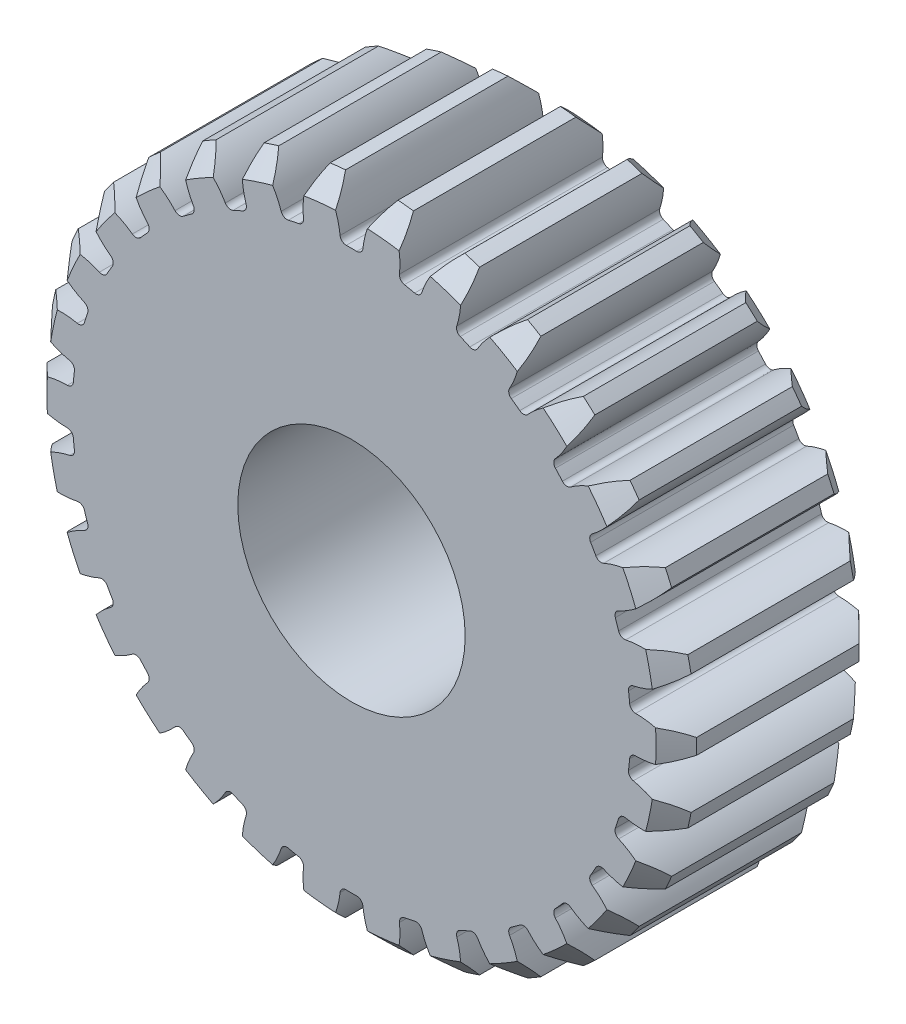
SolidWorks part; units mm, degrees
material "Plain Carbon Steel"
ref_plane "Front Plane" through (0, 0, 0) normal (0, 0, 1) x (1, 0, 0)
ref_plane "Top Plane" through (0, 0, 0) normal (0, 1, 0) x (1, 0, 0)
ref_plane "Right Plane" through (0, 0, 0) normal (1, 0, 0) x (0, 0, -1)
sketch "Sketch1" plane through (0, 0, 0) normal (0, 0, 1) x (1, 0, 0)
  circle A0 centre (0, 0) radius 30 construction
  circle A1 centre (0, 0) radius 32
  dimension "D1" = 60
  dimension "D2" = 64
extrude "Boss-Extrude1" add sketch "Sketch1" along normal mid plane 20
sketch "Sketch2" plane through (0, 0, 10) normal (0, 0, 1) x (1, 0, 0)
  line L0 (0, 0) -> (0, 32) construction
  line L1 (0, 0) -> (6.6532, 31.3007) construction
  line L2 (0, 0) -> (3.3449, 31.8247) construction
  line L3 (-1.0822, 27.4787) -> (0, 0) construction
  line L4 (-1.5701, 29.9589) -> (1.5701, 29.9589) construction
  line L5 (1.5701, 29.9589) -> (4.693, 29.6307) construction
  line L6 (-2.2833, 31.9184) -> (0, 25.6451) construction
  circle A0 centre (0, 0) radius 28 construction
  circle A2 centre (0, 0) radius 32 construction
  arc A3 (-2.5853, 31.8954) -> (-1.0822, 27.4787) centre (-9.2704, 27.1562) cw
  circle A4 centre (0, 0) radius 32 construction
  arc A5 (2.5853, 31.8954) -> (1.0822, 27.4787) centre (9.2704, 27.1562) ccw
  circle A6 centre (0, 0) radius 30 construction
  arc A8 (2.5853, 31.8954) -> (-2.5853, 31.8954) centre (0, 0) ccw
  arc A9 (1.0822, 27.4787) -> (-1.0822, 27.4787) centre (0, 0) ccw
  dimension "D1" = 12
  dimension "D2" = 4
  dimension "D5" = 20
  dimension "D3" = 0.5
extrude "Cut-Extrude1" cut sketch "Sketch2" against normal through all both and the other way through all
chamfer "Chamfer1" distance 2 2 edges at (0, -32, -10) (0, -32, 10)
fillet "Fillet1" radius 0.6 2 edges at (1.0822, 27.4787, 0) (-1.0822, 27.4787, 0)
pattern_circular "CirPattern2" count 30 over 360 about axis through (0, 0, 0) along (0, 0, 1) of "Cut-Extrude1", "Fillet1"
sketch "Sketch3" plane through (0, 0, -10) normal (0, 0, -1) x (-1, 0, 0)
  circle A0 centre (0, 0) radius 11.2
  dimension "D1" = 22.4
extrude "Cut-Extrude2" cut sketch "Sketch3" against normal through all both
equation "\"Module\"= 2"
equation "\"No. of teeth\"= 30"
equation "\"Pressure angle\"= 20"
equation "\"D1@Sketch1\"=\"Module\" * \"No. of teeth\""
equation "\"D2@Sketch1\"=(\"No. of teeth\" + 2 ) * \"Module\""
equation "\"D1@Boss-Extrude1\"= \"Module\" * 10"
equation "\"D1@Sketch2\"= 360 / \"No. of teeth\""
equation "\"D2@Sketch2\"= \"Module\" * 2"
equation "\"D5@Sketch2\"=\"Pressure angle\""
equation "\"D1@Chamfer1\"=\"Module\""
equation "\"D1@Fillet1\"=\"Module\" * 0.3"
equation "\"D1@CirPattern2\"=\"No. of teeth\""
equation "\"D1@Sketch3\"=((\"No. of teeth\" + 2 ) * \"Module\" ) *0.35"
